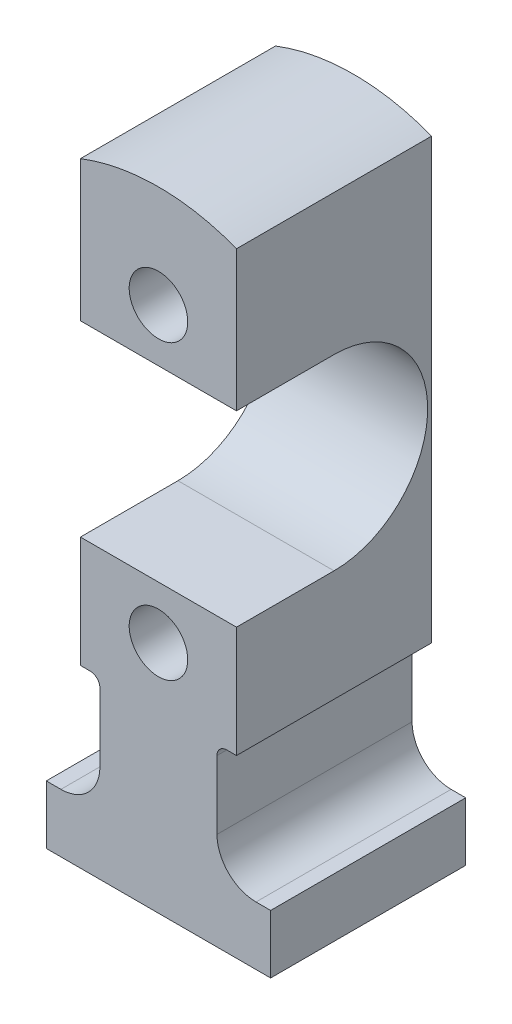
SolidWorks part; units mm, degrees
ref_plane "Front Plane" through (0, 0, 0) normal (0, 0, 1) x (1, 0, 0)
ref_plane "Top Plane" through (0, 0, 0) normal (0, 1, 0) x (1, 0, 0)
ref_plane "Right Plane" through (0, 0, 0) normal (1, 0, 0) x (0, 0, -1)
sketch "Sketch4" plane through (0, 0, 0) normal (0, 0, 1) x (1, 0, 0)
  line L0 (-30, -105) -> (-30, -60)
  line L3 (0, -150) -> (-57.5, -150)
  line L4 (0, -150) -> (57.5, -150)
  line L5 (57.5, -150) -> (57.5, -120)
  line L6 (57.5, -120) -> (-57.5, -120)
  line L7 (-57.5, -120) -> (-57.5, -150)
  line L8 (30, -105) -> (30, -60)
  line L9 (0, -105) -> (-30, -105)
  line L10 (-30, -105) -> (-30, -120)
  line L11 (0, -105) -> (30, -105)
  line L12 (30, -105) -> (30, -120)
  line L13 (-40, -60) -> (-40, 165)
  line L14 (0, -60) -> (-40, -60)
  line L15 (0, -60) -> (40, -60)
  line L16 (40, -60) -> (40, 165)
  line L17 (40, 165) -> (39.9586, 165)
  line L18 (-39.9586, 165) -> (-40, 165)
  arc A3 (40, 164.9839) -> (-40, 164.9839) centre (0, 62.0133) ccw
extrude "Boss-Extrude1" add sketch "Sketch4" along normal blind 100 contours L16 A3 L13 L14 L15 | L15 L14 L0 L9 L11 L8 | L6 L7 L3 L4 L5 | L12 L11 L9 L10 L6
fillet "Fillet1" radius 5 1 edges at (-30, -60, 50)
fillet "Fillet2" radius 5 1 edges at (30, -60, 50)
fillet "Fillet3" radius 20 1 edges at (-30, -120, 50)
fillet "Fillet4" radius 20 1 edges at (30, -120, 50)
sketch "Sketch5" plane through (0, 0, 100) normal (0, 0, 1) x (1, 0, 0)
  line L3 (0, 105) -> (0, 120)
  circle A3 centre (0, 120) radius 15
extrude "Cut-Extrude1" cut sketch "Sketch5" against normal through all contours A3
sketch "Sketch16" plane through (0, 0, 100) normal (0, 0, 1) x (1, 0, 0)
  circle A0 centre (0, -30) radius 15
extrude "Cut-Extrude5" cut sketch "Sketch16" against normal through all
sketch "Sketch19" plane through (0, 0, 0) normal (1, 0, 0) x (0, 0, -1)
  line L0 (-50, 93) -> (-100, 93)
  line L2 (-100, -60) -> (-100, 164.9839) construction
  line L4 (-50, -3) -> (-100, -3)
  line L5 (-100, -3) -> (-100, 93)
  arc A0 (-50, -3) -> (-50, 93) centre (-50, 45) ccw
extrude "Cut-Extrude8" cut sketch "Sketch19" against normal through all and the other way through all
